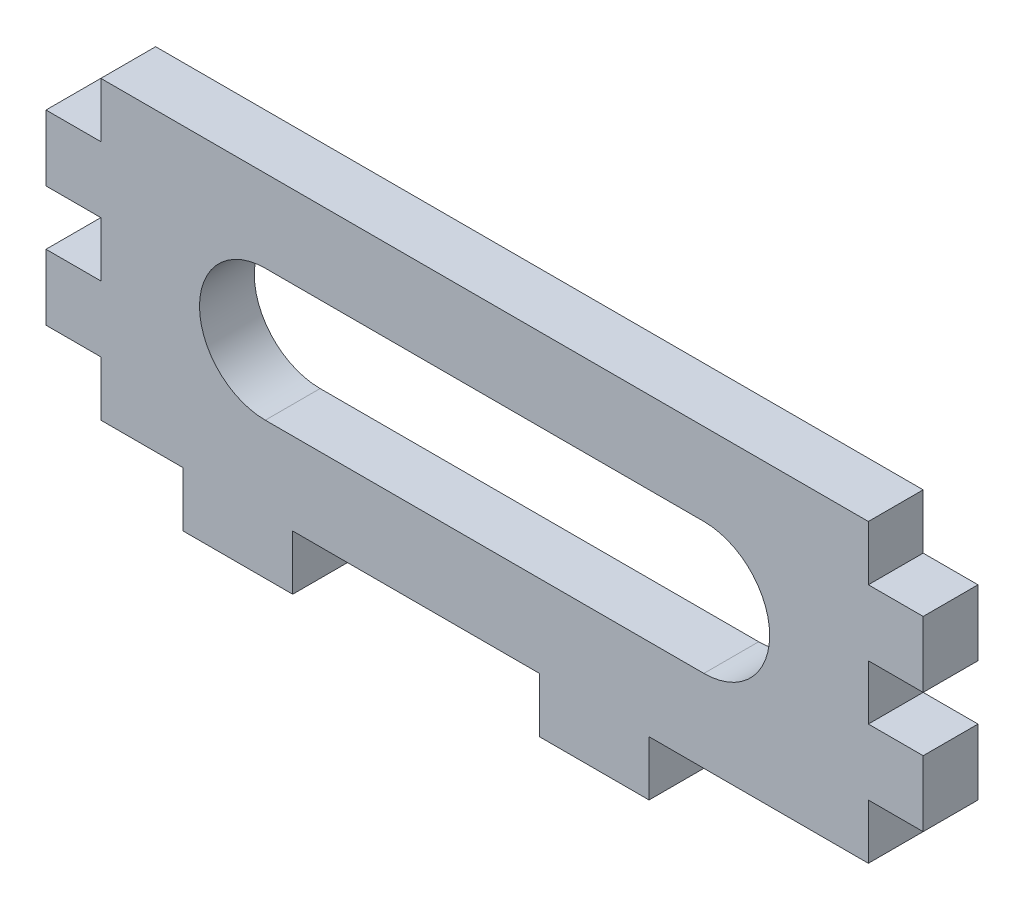
SolidWorks part; units mm, degrees
material "Balsa"
ref_plane "Plan de face" through (0, 0, 0) normal (0, 0, 1) x (1, 0, 0)
ref_plane "Plan de dessus" through (0, 0, 0) normal (0, 1, 0) x (1, 0, 0)
ref_plane "Plan de droite" through (0, 0, 0) normal (1, 0, 0) x (0, 0, -1)
sketch "Esquisse1" plane through (0, 0, 0) normal (0, 0, 1) x (1, 0, 0)
  line L1 (121.1746, 170.4211) -> (201.1746, 170.4211)
  line L2 (121.1746, 170.4211) -> (121.1746, 143.4211)
  line L3 (121.1746, 143.4211) -> (201.1746, 143.4211)
  line L4 (201.1746, 170.4211) -> (201.1746, 143.4211)
extrude "Boss.-Extru.1" add sketch "Esquisse1" against normal blind 5
sketch "Esquisse2" plane through (0, 0, 0) normal (0, 0, 1) x (1, 0, 0)
  line L0 (121.1746, 170.4211) -> (121.1746, 143.4211) construction
  line L1 (126.1746, 165.4211) -> (121.1746, 165.4211)
  line L2 (126.1746, 165.4211) -> (126.1746, 170.4211)
  line L3 (126.1746, 170.4211) -> (121.1746, 170.4211)
  line L4 (121.1746, 165.4211) -> (121.1746, 170.4211)
  line L5 (121.1746, 143.4211) -> (201.1746, 143.4211) construction
  line L6 (121.1746, 159.4211) -> (126.1746, 159.4211)
  line L7 (121.1746, 159.4211) -> (121.1746, 154.4211)
  line L8 (121.1746, 154.4211) -> (126.1746, 154.4211)
  line L9 (126.1746, 159.4211) -> (126.1746, 154.4211)
  line L10 (121.1746, 148.4211) -> (126.1746, 148.4211)
  line L11 (121.1746, 148.4211) -> (121.1746, 143.4211)
  line L12 (121.1746, 143.4211) -> (126.1746, 143.4211)
  line L13 (126.1746, 148.4211) -> (126.1746, 143.4211)
  line L14 (161.1746, 223.4211) -> (161.1746, 138.4211) construction
  line L15 (201.1746, 170.4211) -> (121.1746, 170.4211) construction
  line L16 (196.1746, 148.4211) -> (196.1746, 143.4211)
  line L17 (201.1746, 143.4211) -> (196.1746, 143.4211)
  line L18 (201.1746, 148.4211) -> (201.1746, 143.4211)
  line L19 (201.1746, 148.4211) -> (196.1746, 148.4211)
  line L20 (196.1746, 159.4211) -> (196.1746, 154.4211)
  line L21 (201.1746, 154.4211) -> (196.1746, 154.4211)
  line L22 (201.1746, 159.4211) -> (201.1746, 154.4211)
  line L23 (201.1746, 159.4211) -> (196.1746, 159.4211)
  line L24 (201.1746, 165.4211) -> (201.1746, 170.4211)
  line L25 (196.1746, 170.4211) -> (201.1746, 170.4211)
  line L26 (196.1746, 165.4211) -> (196.1746, 170.4211)
  line L27 (196.1746, 165.4211) -> (201.1746, 165.4211)
  line L28 (141.1746, 156.9211) -> (181.1746, 156.9211) construction
  line L29 (141.1746, 162.9211) -> (181.1746, 162.9211)
  line L30 (141.1746, 150.9211) -> (181.1746, 150.9211)
  arc A0 (141.1746, 162.9211) -> (141.1746, 150.9211) centre (141.1746, 156.9211) ccw
  arc A1 (181.1746, 150.9211) -> (181.1746, 162.9211) centre (181.1746, 156.9211) ccw
  point P34 (161.1746, 156.9211)
  dimension "D6" = 6
  dimension "D1" = 5
  dimension "D2" = 5
  dimension "D3" = 6
  dimension "D4" = 6
  dimension "D5" = 40
  dimension "D7" = 13.5
extrude "Créneaux -" cut sketch "Esquisse2" against normal blind 5
sketch "Esquisse3" plane through (0, 0, 0) normal (0, 0, 1) x (1, 0, 0)
  line L0 (126.1746, 143.4211) -> (196.1746, 143.4211) construction
  line L1 (133.6746, 143.4211) -> (143.6746, 143.4211)
  line L2 (133.6746, 143.4211) -> (133.6746, 138.4211)
  line L3 (133.6746, 138.4211) -> (143.6746, 138.4211)
  line L4 (143.6746, 143.4211) -> (143.6746, 138.4211)
  line L5 (161.1746, 223.4211) -> (161.1746, 138.4211) construction
  line L6 (166.1746, 143.4211) -> (176.1746, 143.4211)
  line L7 (166.1746, 143.4211) -> (166.1746, 138.4211)
  line L8 (166.1746, 138.4211) -> (176.1746, 138.4211)
  line L9 (176.1746, 143.4211) -> (176.1746, 138.4211)
  dimension "D1" = 17.5
  dimension "D2" = 5
  dimension "D3" = 5
  dimension "D4" = 10
  dimension "D5" = 10
extrude "Boss.-Extru.2" add sketch "Esquisse3" against normal blind 5
